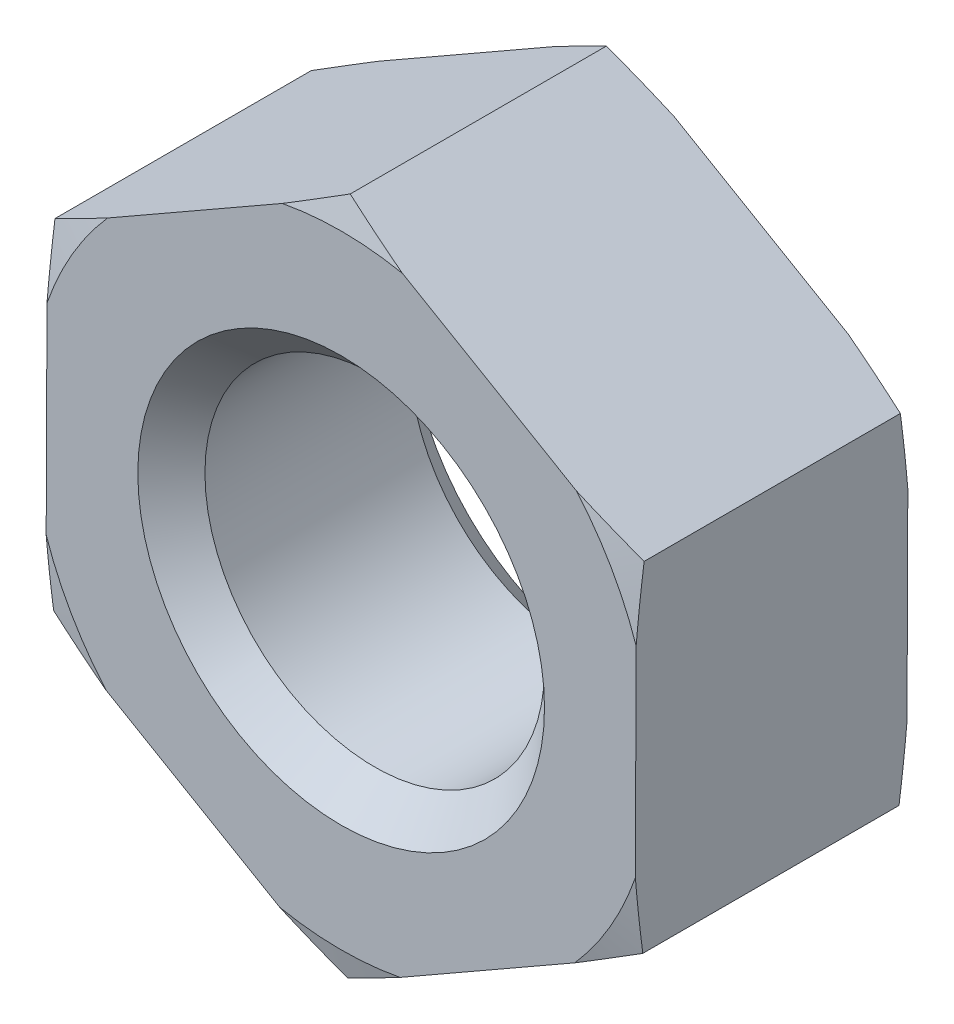
SolidWorks part; units mm, degrees
extrude "基体-拉伸" add sketch "草图1" along normal blind 2.4
sketch "草图1" plane through (0, 0, 0) normal (0, 0, 1) x (1, 0, 0)
  line L0 (-26.8088, 0) -> (37.1748, 0) construction
  line L1 (0, 25.0215) -> (0, -25.0215) construction
  line L3 (0.0118, 3.005) -> (-2.5965, 1.5127)
  line L4 (-2.5965, 1.5127) -> (-2.6083, -1.4923)
  line L5 (-2.6083, -1.4923) -> (-0.0118, -3.005)
  line L6 (-0.0118, -3.005) -> (2.5965, -1.5127)
  line L7 (2.5965, -1.5127) -> (2.6083, 1.4923)
  line L8 (2.6083, 1.4923) -> (0.0118, 3.005)
  circle A0 centre (0, 0) radius 2.6024 construction
  circle A1 centre (0, 0) radius 1.5
  dimension "D" = 3
  dimension "e" = 6.01
cosmetic thread "装饰螺纹线1"
chamfer "倒角1" distance 0.2964 angle 45 2 edges at (1.5, 0, 0) (1.5, 0, 2.4)
material "A2-70级"
ref_plane "基准面1" through (0, 0, 0) normal (0, 0, 1) x (1, 0, 0)
ref_plane "基准面2" through (0, 0, 0) normal (0, 1, 0) x (1, 0, 0)
ref_plane "基准面3" through (0, 0, 0) normal (1, 0, 0) x (0, 0, -1)
sketch "尺寸草图" plane through (0, 0, 0) normal (0, 0, 1) x (1, 0, 0)
  line L0 (0, 0) -> (33.9749, 0)
  line L1 (33.9749, 0) -> (37.4249, 0)
  line L2 (37.4249, 0) -> (42.0249, 0)
  line L3 (-2.8571, 0) -> (0, 0)
  point P3 (3, 0)
  point P4 (1.5, 0)
  point P5 (6.01, 0)
  point P6 (2.4, 0)
  point P7 (6.4, 0)
  point P8 (5.5, 0)
  dimension "D" = 3
  dimension "e" = 6.01
  dimension "P" = 1.5
  dimension "m" = 2.4
  dimension "mw" = 6.4
  dimension "s" = 5.5
  dimension "da" = 3.45
  dimension "dw" = 4.6
  dimension "D1" = 2.8571
sketch "草图2" plane through (0, 0, 0) normal (0, 0, -1) x (-1, 0, 0)
  circle A0 centre (0, 0) radius 2.75
  circle A1 centre (0, 0) radius 1.5 construction
  dimension "s" = 5.5
extrude "切除-拉伸1" cut sketch "草图2" against normal through all draft 75 flip side to cut
sketch "草图3" plane through (0, 0, 2.4) normal (0, 0, 1) x (1, 0, 0)
  circle A0 centre (0, 0) radius 2.75
  dimension "D1" = 5.5
extrude "切除-拉伸2" cut sketch "草图3" against normal through all draft 75 flip side to cut
equation "\"e@草图1\" = \"e@尺寸草图\""
equation "\"D1@尺寸草图\" = \"D@尺寸草图\" / 1.05"
equation "\"D@草图1\" = \"D@尺寸草图\""
equation "\"m@基体-拉伸\" = \"m@尺寸草图\""
equation "\"D1@草图3\" = \"s@尺寸草图\""
equation "\"s@草图2\" = \"s@尺寸草图\""
equation "\"D2@装饰螺纹线1\" =\"D@尺寸草图\""
equation "\"D1@倒角1\" =  ( \"da@尺寸草图\" - \"D1@尺寸草图\" )  / 2"
